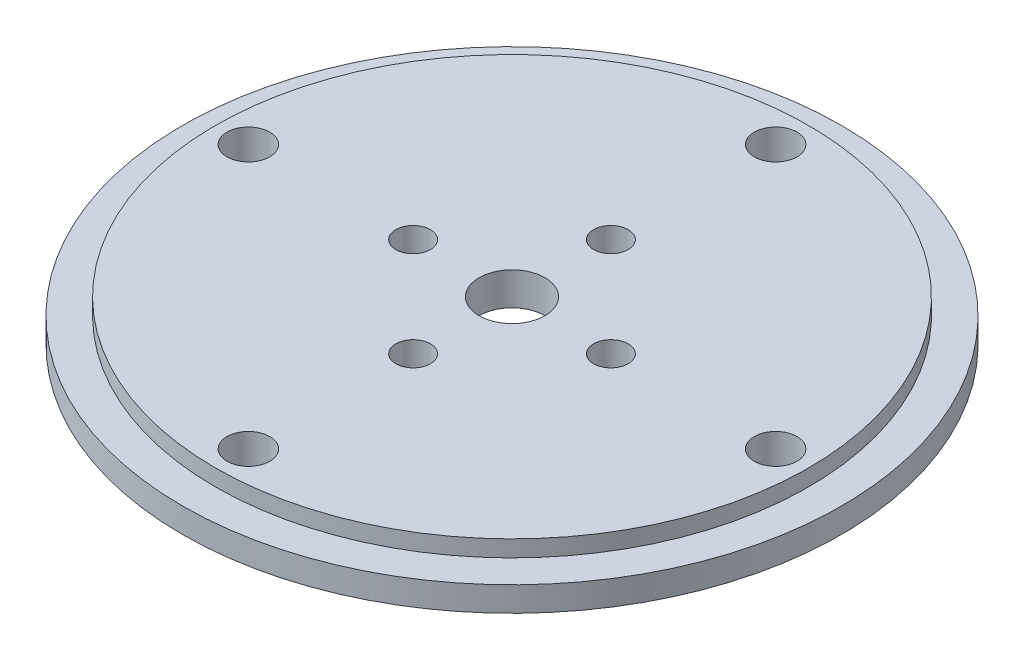
SolidWorks part; units mm, degrees
ref_plane "前视基准面" through (0, 0, 0) normal (0, 0, 1) x (1, 0, 0)
ref_plane "上视基准面" through (0, 0, 0) normal (0, 1, 0) x (1, 0, 0)
ref_plane "右视基准面" through (0, 0, 0) normal (1, 0, 0) x (0, 0, -1)
other "Configuration Table"
sketch "草图1" plane through (0, 0, 0) normal (0, 1, 0) x (1, 0, 0)
  circle A0 centre (0, 0) radius 40
  dimension "D1" = 80
extrude "凸台-拉伸1" add sketch "草图1" along normal blind 3
sketch "草图2" plane through (0, 3, 0) normal (0, 1, 0) x (1, 0, 0)
  circle A0 centre (0, 0) radius 36
  dimension "D1" = 72
extrude "凸台-拉伸2" add sketch "草图2" along normal blind 2
sketch "草图3" plane through (0, 0, 0) normal (0, -1, 0) x (1, 0, 0)
  circle A0 centre (-12, 0) radius 2.1
  circle A1 centre (0, 12) radius 2.1
  circle A2 centre (12, 0) radius 2.1
  circle A3 centre (0, -12) radius 2.1
  circle A4 centre (0, 0) radius 4
  point P12 (0, 0)
  dimension "D1" = 12
  dimension "D2" = 4.2
  dimension "D4" = 8
  dimension "D3" = 4
extrude "切除-拉伸1" cut sketch "草图3" against normal through all both and the other way through all
sketch "草图4" plane through (0, 0, 0) normal (0, -1, 0) x (1, 0, 0)
  circle A0 centre (0, 0) radius 16.1
  dimension "D1" = 32.2
extrude "切除-拉伸2" cut sketch "草图4" against normal blind 1
sketch "草图5" plane through (0, 0, 0) normal (0, -1, 0) x (1, 0, 0)
  circle A0 centre (-32, 0) radius 2.6
  circle A1 centre (0, 32) radius 2.6
  circle A2 centre (32, 0) radius 2.6
  circle A3 centre (0, -32) radius 2.6
  point P12 (0, 0)
  dimension "D1" = 5.2
  dimension "D2" = 32
  dimension "D3" = 4
extrude "切除-拉伸3" cut sketch "草图5" against normal through all
sketch "草图6" plane through (0, 0, 0) normal (0, -1, 0) x (1, 0, 0)
  circle A0 centre (0, -32) radius 5
  circle A1 centre (0, -32) radius 2.6
  circle A2 centre (0, -32) radius 2.6 construction
  circle A3 centre (32, 0) radius 2.6
  circle A4 centre (32, 0) radius 2.6 construction
  circle A5 centre (0, 32) radius 2.6
  circle A6 centre (0, 32) radius 2.6 construction
  circle A7 centre (-32, 0) radius 2.6
  circle A8 centre (-32, 0) radius 2.6 construction
  circle A9 centre (32, 0) radius 5
  circle A10 centre (0, 32) radius 5
  circle A11 centre (-32, 0) radius 5
  dimension "D1" = 0
  dimension "D2" = 0
  dimension "D3" = 0
  dimension "D4" = 0
  dimension "D5" = 2.4
extrude "切除-拉伸4" cut sketch "草图6" against normal blind 1
